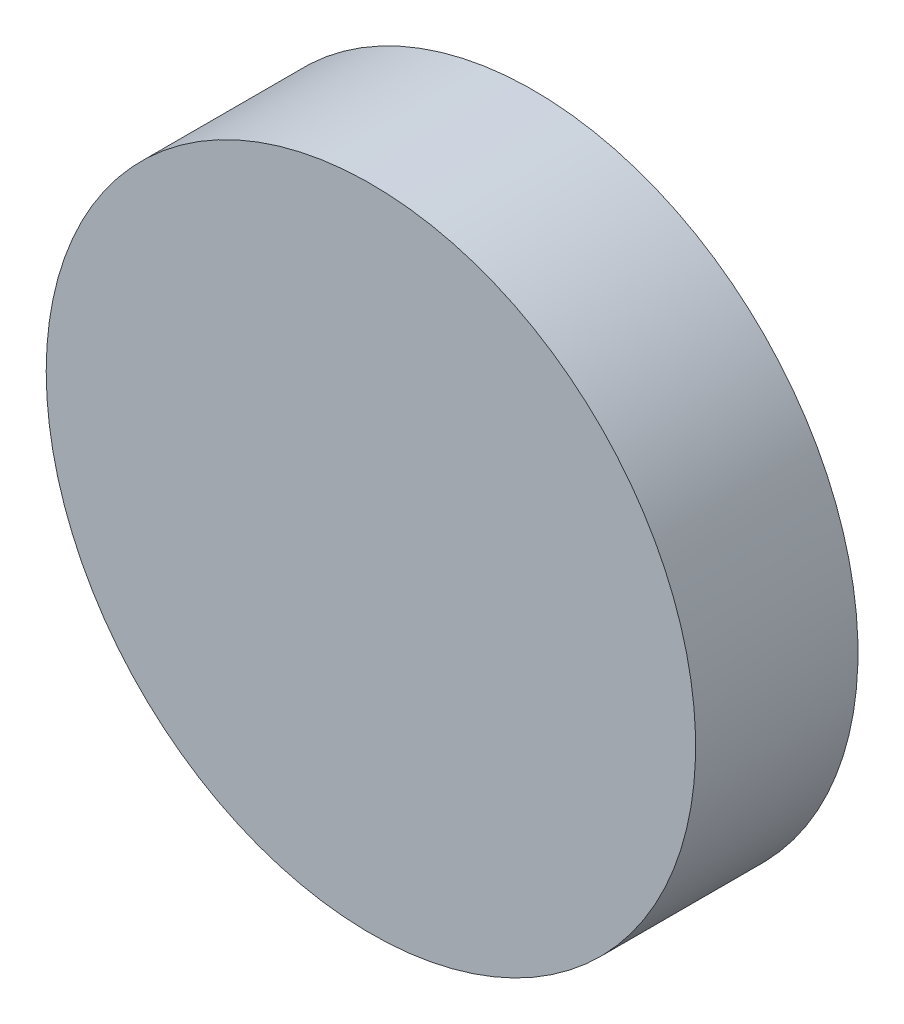
SolidWorks part; units mm, degrees
ref_plane "Front Plane" through (0, 0, 0) normal (0, 0, 1) x (1, 0, 0)
ref_plane "Top Plane" through (0, 0, 0) normal (0, 1, 0) x (1, 0, 0)
ref_plane "Right Plane" through (0, 0, 0) normal (1, 0, 0) x (0, 0, -1)
sketch "Sketch1" plane through (0, 0, 0) normal (0, 1, 0) x (1, 0, 0)
  line L5 (-4, 2) -> (0, 2)
  line L8 (0, 2) -> (0, 0)
  line L9 (0, 0) -> (-4, 0)
  line L10 (-4, 0) -> (-4, 2)
  point P0 (0, 0)
  dimension "D1" = 4
  dimension "D2" = 2
revolve "Revolve1" add sketch "Sketch1" angle 360 about L8
